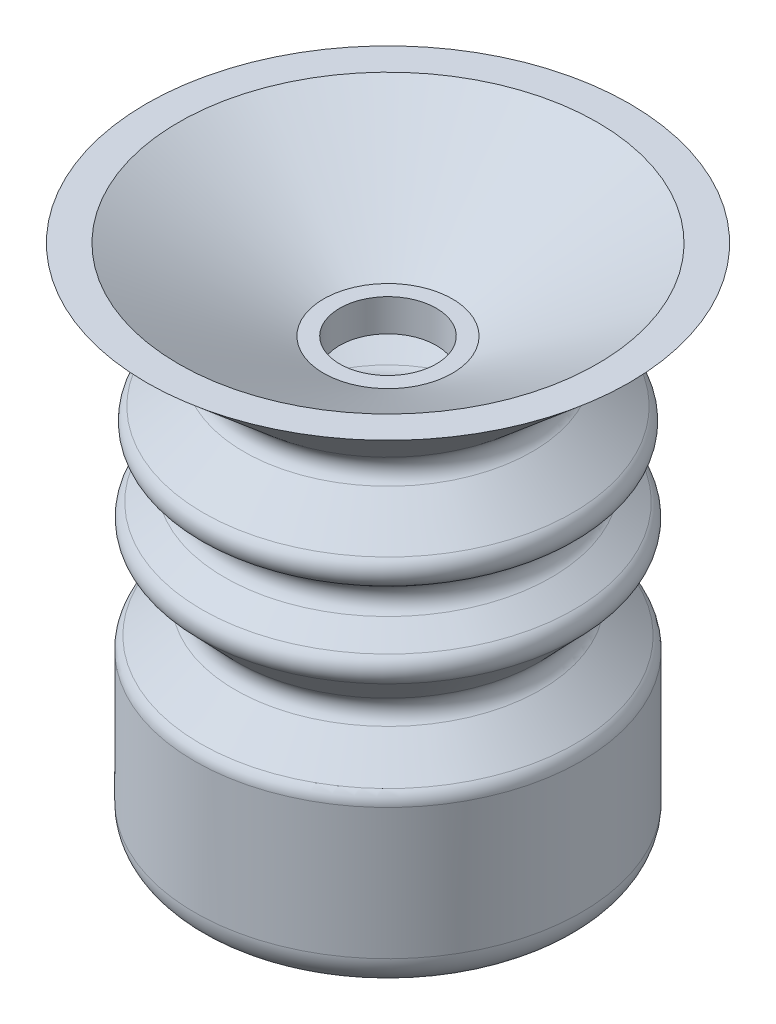
SolidWorks part; units mm, degrees
material "PE très faible densité (SS)"
ref_plane "Front" through (0, 0, 0) normal (0, 0, 1) x (1, 0, 0)
ref_plane "Top" through (0, 0, 0) normal (0, 1, 0) x (1, 0, 0)
ref_plane "Right" through (0, 0, 0) normal (1, 0, 0) x (0, 0, -1)
sketch "Esquisse1" plane through (0, 0, 0) normal (0, 0, 1) x (1, 0, 0)
  line L0 (0, 0) -> (0, 16) construction
  line L1 (2.5, 0) -> (2.5, 3)
  line L4 (6.5, 16) -> (7.5, 16)
  line L5 (7.5, 16) -> (4, 13)
  line L10 (6, 5.3) -> (6, 0)
  line L11 (6, 0) -> (2.5, 0)
  line L12 (2, 13.5) -> (6.5, 16)
  line L13 (2.5, 5) -> (2.5, 7.3)
  line L14 (2.5, 5) -> (3.5, 5)
  line L16 (2.5, 3) -> (3.5, 3)
  line L17 (3.5, 5) -> (3.5, 3)
  line L18 (14.788, 243.268) -> (-140.5453, 243.268) construction
  line L19 (2, 13.5) -> (1.5, 13.5)
  line L20 (1.5, 13.5) -> (1.5, 12.5)
  line L21 (1.5, 12.5) -> (3.0242, 12.5)
  line L22 (3.0242, 12.5) -> (4.6492, 11.2)
  line L23 (4.6492, 11.2) -> (2.8394, 9.9073)
  line L24 (2.8394, 9.9073) -> (4.5295, 8.7)
  line L25 (4.5295, 8.7) -> (2.5, 7.3)
  line L26 (4, 13) -> (6.25, 11.2)
  line L27 (6.25, 11.2) -> (4.5, 9.95)
  line L28 (4.5, 9.95) -> (6.25, 8.7)
  line L29 (6.25, 8.7) -> (4.3315, 6.7)
  line L30 (4.3315, 6.7) -> (6, 5.3)
  dimension "D2" = 16
  dimension "D3" = 5
  dimension "D4" = 12
  dimension "D5" = 2.5
  dimension "D6" = 3
  dimension "D7" = 1
  dimension "D8" = 15
  dimension "D9" = 1
  dimension "D10" = 0.5
  dimension "D11" = 3
  dimension "D12" = 4.8
  dimension "D13" = 2.5
  dimension "D14" = 7
  dimension "D15" = 3
  dimension "D16" = 2
  dimension "D17" = 5.3
  dimension "D18" = 12.5
  dimension "D19" = 6.7
  dimension "D20" = 50
  dimension "D21" = 2.3
  dimension "D22" = 8
  dimension "D23" = 9
  dimension "D24" = 1
  dimension "D25" = 1
revolve "Révolution1" add sketch "Esquisse1" angle 360 about L0
fillet "Congé1" radius 0.5 10 edges at (0, 7.3, -2.5) (0, 11.2, -6.25) (0, 5.3, -6) (0, 6.7, -4.3315) (0, 8.7, -6.25) (0, 9.95, -4.5) (0, 11.2, -4.6492) (0, 13, -4) (0, 8.7, -4.5295) (0, 9.9073, -2.8394)
fillet "Congé2" radius 1 1 edges at (0, 0, -6)
sketch "Esquisse2" plane through (0, 0, 0) normal (0, 0, 1) x (1, 0, 0)
  line L0 (0, -50) -> (0, 50) construction
  line L1 (-5, 0) -> (5, 0) construction
  point P0 (0, 11)
  dimension "D1" = 11
